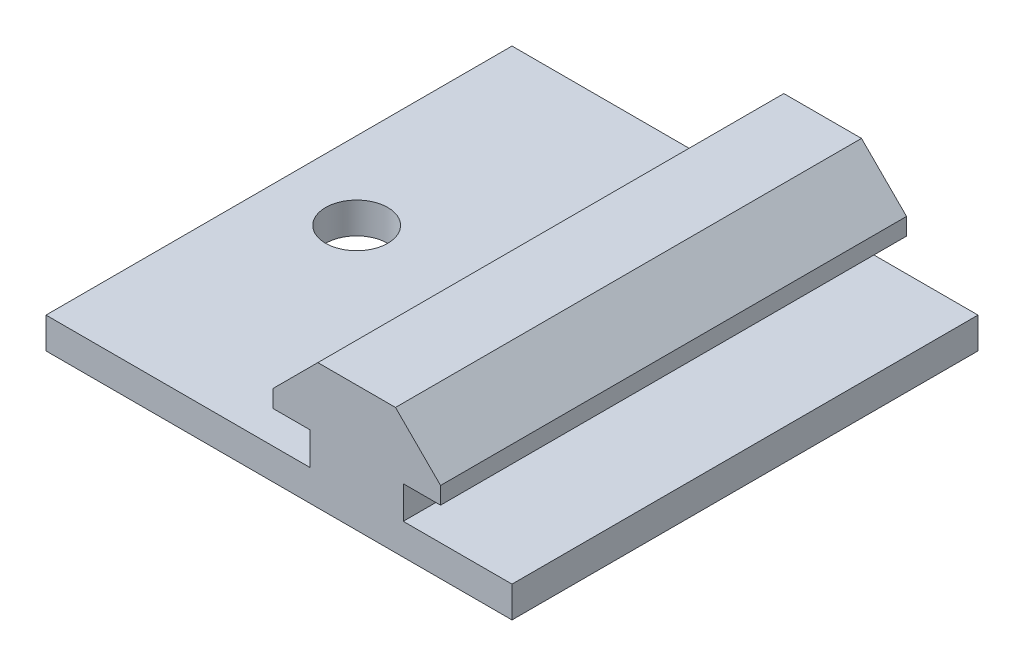
SolidWorks part; units mm, degrees
ref_plane "Front Plane" through (0, 0, 0) normal (0, 0, 1) x (1, 0, 0)
ref_plane "Top Plane" through (0, 0, 0) normal (0, 1, 0) x (1, 0, 0)
ref_plane "Right Plane" through (0, 0, 0) normal (1, 0, 0) x (0, 0, -1)
sketch "Sketch2" plane through (0, 0, 0) normal (0, 0, 1) x (1, 0, 0)
  line L0 (5.4, 3.2) -> (2.5, 6.1)
  line L1 (5.4, 2.1) -> (5.4, 3.2)
  line L2 (-3, 2.1) -> (-3, 0)
  line L3 (3, 2.1) -> (5.4, 2.1)
  line L5 (-3, 2.1) -> (-5.4, 2.1)
  line L6 (-5.4, 2.1) -> (-5.4, 3.2)
  line L7 (-5.4, 3.2) -> (-2.5, 6.1)
  line L8 (-2.5, 6.1) -> (2.5, 6.1)
  line L9 (0, -55) -> (0, 55) construction
  line L18 (-3, 0) -> (-20, 0)
  line L27 (55, 0) -> (-55, 0) construction
  line L29 (3, 2.1) -> (3, 0)
  line L30 (-20, 0) -> (-20, -2)
  line L34 (0, 12.2875) -> (0, -5.4011) construction
  line L38 (-20, -2) -> (10, -2)
  line L40 (3, 0) -> (10, 0)
  line L42 (10, -2) -> (10, 0)
  point P2 (0, 6.1)
  point P19 (9.7974, 0)
  dimension "D1" = 270
  dimension "D2" = 1.1
  dimension "D3" = 10
  dimension "D4" = 20
  dimension "5.4" = 5.4
  dimension "D6" = 4
  dimension "D7" = 2.1
  dimension "D8" = 2
extrude "Boss-Extrude2" add sketch "Sketch2" along normal mid plane 30
sketch "Sketch4" plane through (7, 0, 0) normal (0, -1, 0) x (0, 0, 1)
  line L0 (0, 2.545) -> (0, 11.455) construction
  line L2 (15, 27) -> (-15, 27) construction
  circle A0 centre (0, 22) radius 2
  dimension "D1" = 4
  dimension "D2" = 5
extrude "Cut-Extrude1" cut sketch "Sketch4" along normal through all
